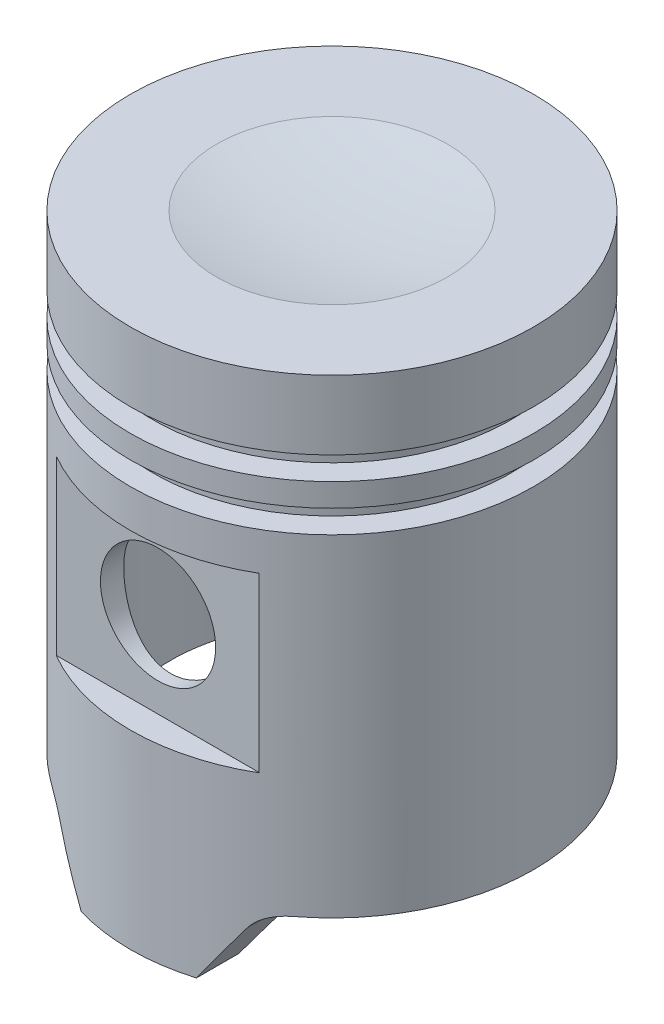
SolidWorks part; units mm, degrees
ref_plane "Front Plane" through (0, 0, 0) normal (0, 0, 1) x (1, 0, 0)
ref_plane "Top Plane" through (0, 0, 0) normal (0, 1, 0) x (1, 0, 0)
ref_plane "Right Plane" through (0, 0, 0) normal (1, 0, 0) x (0, 0, -1)
sketch "Sketch1" plane through (0, 0, 0) normal (0, 0, 1) x (1, 0, 0)
  line L0 (0, 0) -> (0, 58.166)
  line L1 (12.7127, 59.436) -> (22.225, 59.436)
  line L2 (22.225, 59.436) -> (22.225, 51.816)
  line L3 (22.225, 51.816) -> (19.685, 51.816)
  line L4 (19.685, 51.816) -> (19.685, 49.276)
  line L5 (19.685, 49.276) -> (22.225, 49.276)
  line L6 (22.225, 49.276) -> (22.225, 46.736)
  line L7 (22.225, 46.736) -> (19.685, 46.736)
  line L8 (19.685, 46.736) -> (19.685, 44.196)
  line L9 (19.685, 44.196) -> (22.225, 44.196)
  line L10 (22.225, 44.196) -> (22.225, 0)
  line L11 (22.225, 0) -> (0, 0)
  line L12 (0, 59.436) -> (0, 50059.436) construction
  arc A0 (0, 58.166) -> (12.7127, 59.436) centre (0, 122.428) ccw
  point P11 (19.685, 45.466)
  point P14 (22.225, 48.006)
  point P15 (19.685, 50.546)
  dimension "D14" = 128.524
  dimension "D1" = 44.196
  dimension "D2" = 22.225
  dimension "D3" = 7.62
  dimension "D4" = 2.54
  dimension "D5" = 2.54
  dimension "D6" = 2.54
  dimension "D7" = 2.54
  dimension "D8" = 2.54
  dimension "D9" = 2.54
  dimension "D10" = 2.54
  dimension "D11" = 2.54
  dimension "D12" = 2.54
  dimension "D13" = 7.62
revolve "Revolve1" add sketch "Sketch1" angle 360 about L12
sketch "Sketch2" plane through (0, 0, 0) normal (0, 0, 1) x (1, 0, 0)
  line L0 (0, 0) -> (-50000, 0) construction
  line L1 (0, 0) -> (0, -50000) construction
  line L2 (22.225, 0) -> (22.225, 7.62)
  line L3 (22.225, 0) -> (22.225, 44.196) construction
  line L4 (22.225, 7.62) -> (13.4705, 7.62)
  line L5 (-22.225, 0) -> (-22.225, 7.62)
  line L6 (6.35, 0) -> (22.225, 0)
  line L7 (6.35, 0) -> (27748.5714, 41597.7061) construction
  line L8 (6.35, 0) -> (10.3008, 5.924)
  line L9 (-6.35, 0) -> (-22.225, 0)
  line L10 (-6.35, 0) -> (-10.3008, 5.924)
  line L11 (-22.225, 7.62) -> (-13.4705, 7.62)
  arc A0 (13.4705, 7.62) -> (10.3008, 5.924) centre (13.4705, 3.81) ccw
  arc A1 (-13.4705, 7.62) -> (-10.3008, 5.924) centre (-13.4705, 3.81) cw
  dimension "D5" = 3.81
  dimension "D1" = 7.62
  dimension "D2" = 15.875
  dimension "D4" = 236.3
extrude "Cut-Extrude1" cut sketch "Sketch2" against normal through all and the other way through all
sketch "Sketch3" plane through (0, 0, 0) normal (0, -1, 0) x (1, 0, 0)
  circle A0 centre (0, 0) radius 17.78
  dimension "D1" = 35.56
extrude "Cut-Extrude2" cut sketch "Sketch3" against normal blind 51.816
sketch "Sketch4" plane through (0, 0, 0) normal (0, 0, 1) x (1, 0, 0)
  line L0 (0, 0) -> (0, 50000) construction
  circle A0 centre (0, 30.48) radius 6.35
  dimension "D1" = 12.7
  dimension "D2" = 30.48
extrude "Cut-Extrude3" cut sketch "Sketch4" against normal through all and the other way through all
sketch "Sketch5" plane through (0, 0, 0) normal (0, 0, 1) x (1, 0, 0)
  line L0 (0, 0) -> (0, -50000) construction
  line L1 (-11.176, 40.005) -> (11.176, 40.005)
  line L2 (-11.176, 40.005) -> (-11.176, 20.955)
  line L3 (-11.176, 20.955) -> (11.176, 20.955)
  line L4 (11.176, 40.005) -> (11.176, 20.955)
  circle A0 centre (0, 30.48) radius 6.35 construction
  point P9 (-11.176, 30.48)
  dimension "D4" = 9.525
  dimension "D1" = 11.176
  dimension "D2" = 11.176
  dimension "D3" = 19.05
  dimension "D5" = 9.525
extrude "Cut-Extrude4" cut sketch "Sketch5" against normal blind 3.048 from offset 22.225
